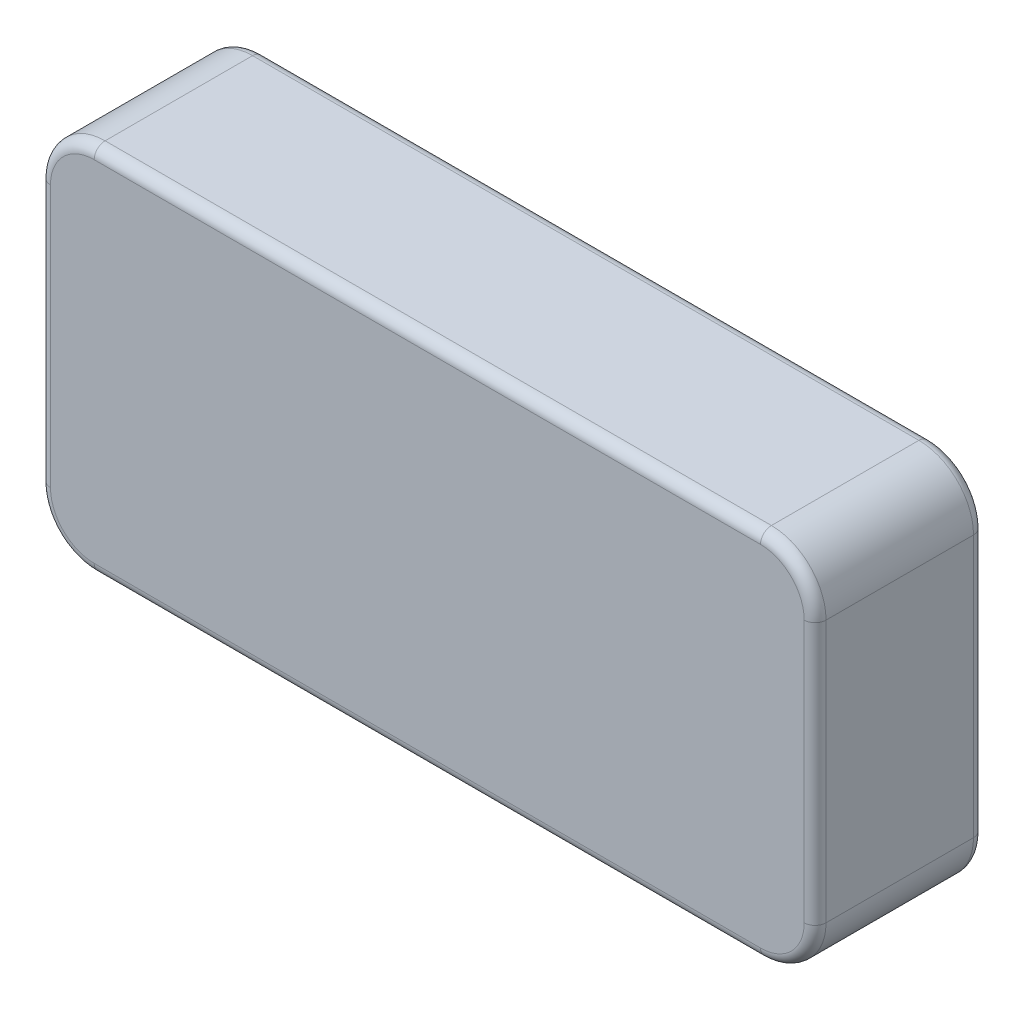
SolidWorks part; units mm, degrees
ref_plane "Front Plane" through (0, 0, 0) normal (0, 0, 1) x (1, 0, 0)
ref_plane "Top Plane" through (0, 0, 0) normal (0, 1, 0) x (1, 0, 0)
ref_plane "Right Plane" through (0, 0, 0) normal (1, 0, 0) x (0, 0, -1)
sketch "Sketch1" plane through (0, 0, 0) normal (0, 0, 1) x (1, 0, 0)
  line L1 (35.5, -17) -> (-35.5, -17)
  line L2 (35.5, -17) -> (35.5, 17)
  line L3 (35.5, 17) -> (-35.5, 17)
  line L4 (-35.5, -17) -> (-35.5, 17)
  line L5 (35.5, -17) -> (-35.5, 17) construction
  line L6 (35.5, 17) -> (-35.5, -17) construction
  point P0 (0, 0)
  dimension "D1" = 34
  dimension "D2" = 71
extrude "Boss-Extrude1" add sketch "Sketch1" along normal blind 15.5
fillet "Fillet1" radius 5 4 edges at (35.5, 17, 7.75) (-35.5, -17, 7.75) (-35.5, 17, 7.75) (35.5, -17, 7.75)
fillet "Fillet2" radius 1 16 edges at (34.0355, -15.5355, 15.5) (0, -17, 15.5) (-34.0355, -15.5355, 15.5) (-35.5, 0, 15.5) (-34.0355, 15.5355, 15.5) (0, 17, 15.5) (34.0355, 15.5355, 15.5) (35.5, 0, 15.5) (-34.0355, 15.5355, 0) (-35.5, 0, 0) (-34.0355, -15.5355, 0) (0, -17, 0) (34.0355, -15.5355, 0) (35.5, 0, 0) (34.0355, 15.5355, 0) (0, 17, 0)
